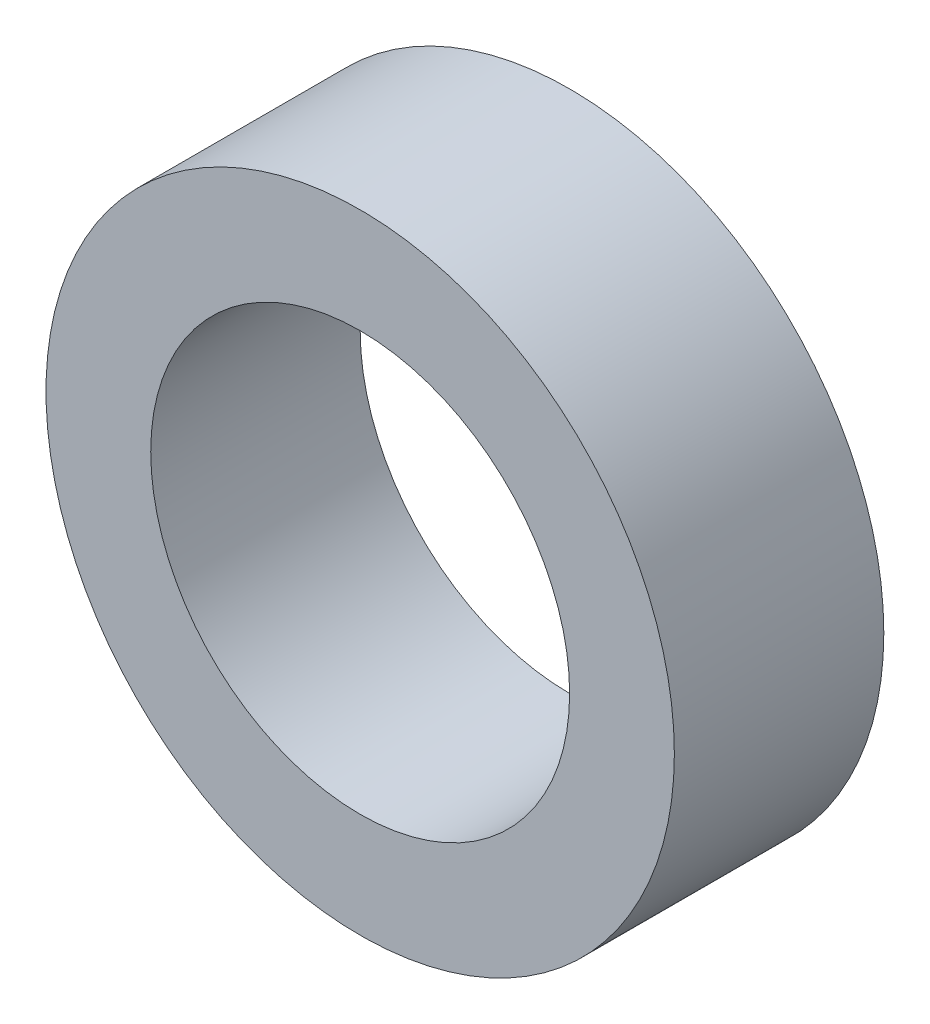
SolidWorks part; units mm, degrees
ref_plane "Front Plane" through (0, 0, 0) normal (0, 0, 1) x (1, 0, 0)
ref_plane "Top Plane" through (0, 0, 0) normal (0, 1, 0) x (1, 0, 0)
ref_plane "Right Plane" through (0, 0, 0) normal (1, 0, 0) x (0, 0, -1)
sketch "Sketch1" plane through (0, 0, 0) normal (0, 0, 1) x (1, 0, 0)
  circle A0 centre (0, 0) radius 5
  circle A1 centre (0, 0) radius 7.5
  dimension "D1" = 10
  dimension "D2" = 15
extrude "Boss-Extrude1" add sketch "Sketch1" along normal blind 5
